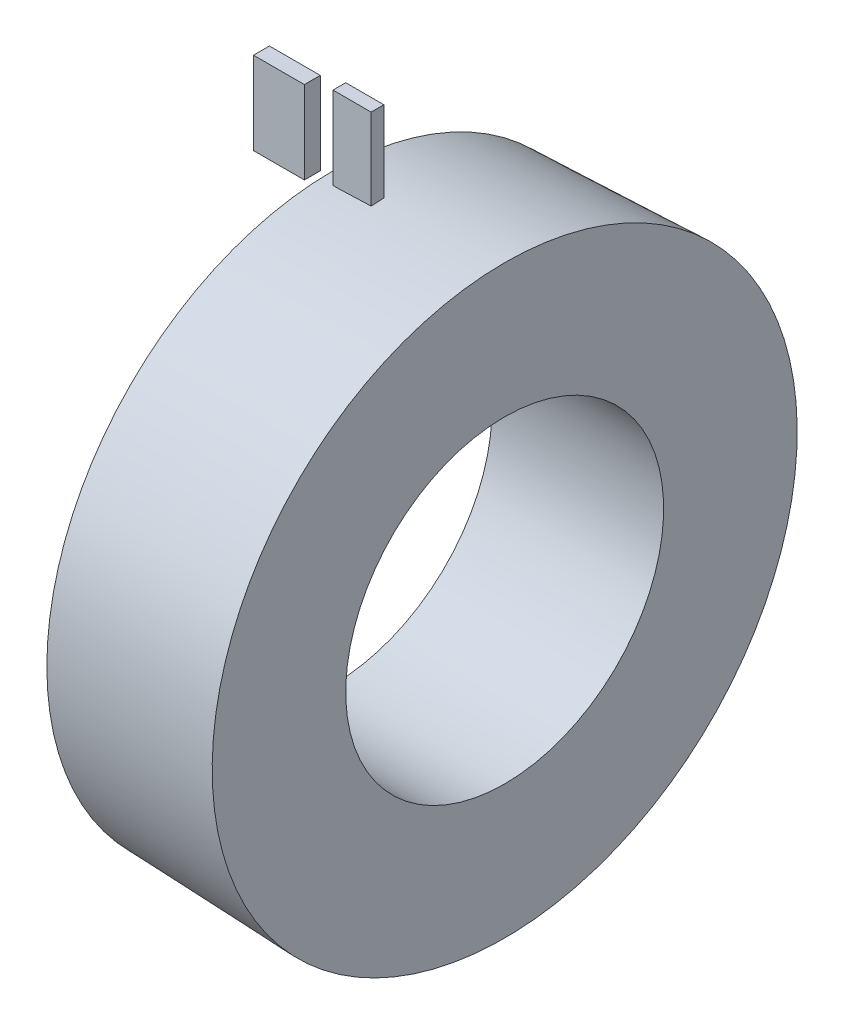
SolidWorks part; units mm, degrees
ref_plane "Front Plane" through (0, 0, 0) normal (0, 0, 1) x (1, 0, 0)
ref_plane "Top Plane" through (0, 0, 0) normal (0, 1, 0) x (1, 0, 0)
ref_plane "Right Plane" through (0, 0, 0) normal (1, 0, 0) x (0, 0, -1)
sketch "Sketch1" plane through (0, 0, 0) normal (0, 0, 1) x (1, 0, 0)
  line L0 (4380, 440) -> (4380, 570)
  line L1 (4380, 570) -> (4460, 570)
  line L2 (4460, 570) -> (4460, 440)
  line L3 (4460, 440) -> (4380, 440)
extrude "Boss-Extrude1" add sketch "Sketch1" along normal blind 25 separate body
sketch "Sketch2" plane through (0, 0, 0) normal (0, 0, 1) x (1, 0, 0)
  line L0 (0, 0) -> (5500, 0) construction
  line L1 (4480, 250) -> (4480, 450)
  line L2 (4480, 450) -> (4750, 460)
  line L3 (4750, 460) -> (4750, 250)
  line L4 (4750, 250) -> (4480, 250)
revolve "Revolve1" add sketch "Sketch2" angle 360 about L0
sketch "Sketch3" plane through (0, 0, 0) normal (0, 0, 1) x (1, 0, 0)
  line L0 (4500, 450) -> (4500, 580)
  line L1 (4500, 580) -> (4560, 580)
  line L2 (4560, 580) -> (4560, 450)
  line L3 (4560, 450) -> (4500, 450)
extrude "Boss-Extrude2" add sketch "Sketch3" along normal blind 20 separate body
